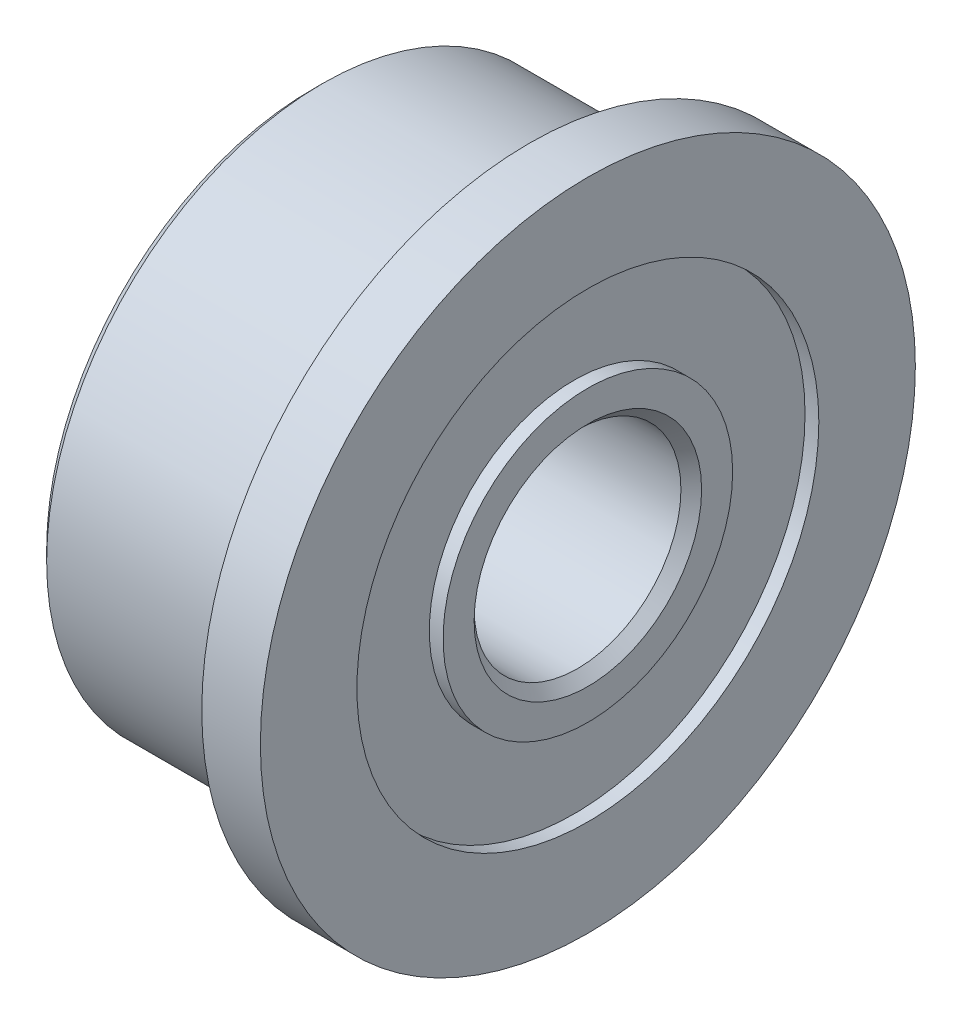
SolidWorks part; units mm, degrees
other "Defeature"
material "Alloy Steel"
ref_plane "Front Plane" through (0, 0, 0) normal (0, 0, 1) x (1, 0, 0)
ref_plane "Top Plane" through (0, 0, 0) normal (0, 1, 0) x (1, 0, 0)
ref_plane "Right Plane" through (0, 0, 0) normal (1, 0, 0) x (0, 0, -1)
sketch "Sketch1" plane through (0, 0, 0) normal (0, 0, 1) x (1, 0, 0)
  line L0 (0, 0) -> (-4, 0) construction
  line L1 (2.2, 0) -> (-2.2, 0) construction
  line L2 (-4, 1.5) -> (0, 1.5)
  line L3 (0, 1.5) -> (0, 2.1)
  line L4 (0, 4.75) -> (-0.85, 4.75)
  line L5 (-0.85, 4.75) -> (-0.85, 4.02)
  line L6 (-0.87, 4) -> (-4, 4)
  line L7 (-4, 4) -> (-4, 3.35)
  line L8 (0, -5.225) -> (0, 5.225) construction
  line L9 (-4, 2.1) -> (-4, 1.5)
  line L10 (-4, 3.35) -> (-3.8, 3.35)
  line L11 (0, 3.35) -> (0, 4.75)
  line L12 (-4, 2.1) -> (-3.8, 2.1)
  line L13 (-3.8, 3.35) -> (-3.8, 2.1)
  line L14 (-0.2, 3.35) -> (0, 3.35)
  line L15 (-0.2, 3.35) -> (-0.2, 2.1)
  line L16 (-0.2, 2.1) -> (0, 2.1)
  arc A0 (-0.87, 4) -> (-0.85, 4.02) centre (-0.85, 4) ccw
  dimension "D6" = 0.02
  dimension "D1" = 3
  dimension "D2" = 8
  dimension "D3" = 9.5
  dimension "D4" = 0.85
  dimension "D5" = 4
  dimension "D7" = 4.2
  dimension "D8" = 6.7
  dimension "D9" = 0.2
revolve "Revolve1" add sketch "Sketch1" angle 360 about L0
chamfer "Chamfer1" distance 0.15 angle 45 3 edges at (0, 0, -1.5) (-4, 0, -1.5) (-4, 0, -4)
